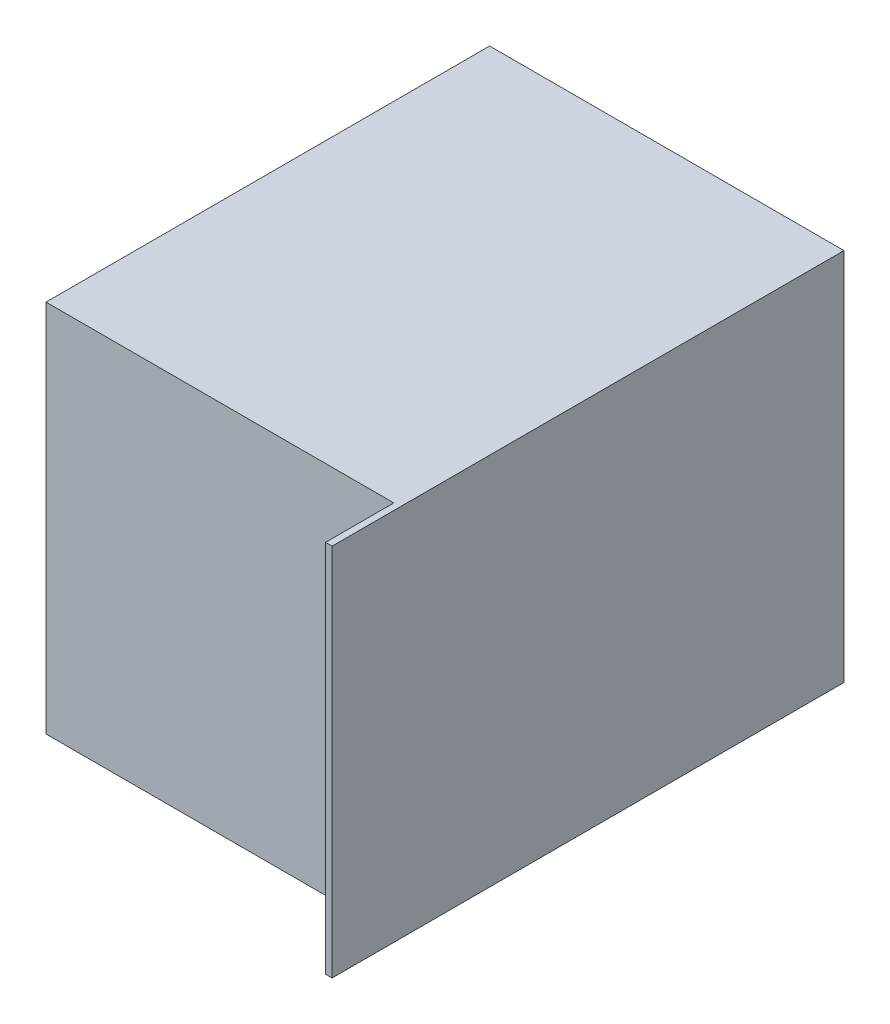
SolidWorks part; units mm, degrees
material "Thornel Mat VMA"
ref_plane "Plano frontal" through (0, 0, 0) normal (0, 0, 1) x (1, 0, 0)
ref_plane "Plano superior" through (0, 0, 0) normal (0, 1, 0) x (1, 0, 0)
ref_plane "Plano direito" through (0, 0, 0) normal (1, 0, 0) x (0, 0, -1)
sketch "Esboço1" plane through (0, 0, 0) normal (0, 1, 0) x (1, 0, 0)
  line L0 (-41.4274, -28.6) -> (11.5726, -28.6)
  line L1 (11.5726, -39) -> (12.5726, -39)
  line L2 (-41.4274, -28.6) -> (-41.4274, 39)
  line L3 (-41.4274, 39) -> (12.5726, 39)
  line L4 (12.5726, -39) -> (12.5726, 39)
  line L7 (11.5726, -28.6) -> (11.5726, -39)
  point P0 (0, 0)
  dimension "D1" = 78
  dimension "D2" = 54
  dimension "D3" = 67.6
  dimension "D4" = 53
extrude "Ressalto-extrusão1" add sketch "Esboço1" along normal blind 57
sketch "Esboço2" plane through (0, 0, 0) normal (0, -1, 0) x (1, 0, 0)
  line L0 (-41.4274, 28.6) -> (11.5726, 28.6) construction
  line L1 (-41.4274, -39) -> (-41.4274, 28.6) construction
  circle A0 centre (-31.6774, 12.75) radius 1.75
  dimension "D1" = 3.5
  dimension "D2" = 15.85
  dimension "D3" = 9.75
extrude "Corte-extrusão1" cut sketch "Esboço2" against normal blind 10
